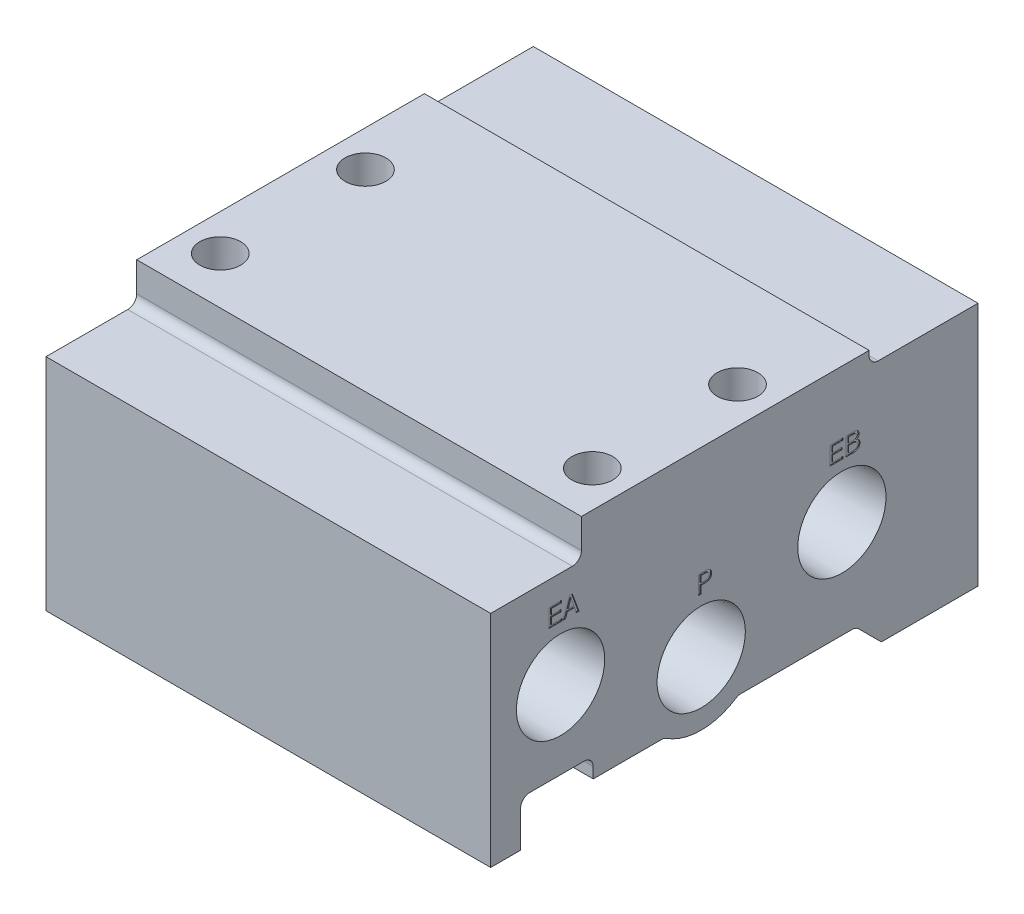
SolidWorks part; units mm, degrees
material "6061-T6 (SS)"
ref_plane "Front" through (0, 0, 0) normal (0, 0, 1) x (1, 0, 0)
ref_plane "Top" through (0, 0, 0) normal (0, 1, 0) x (1, 0, 0)
ref_plane "Right" through (0, 0, 0) normal (1, 0, 0) x (0, 0, -1)
sketch "Alum Ext Sketch" plane through (0, 0, 0) normal (1, 0, 0) x (0, 0, -1)
  line L1 (-26.85, 0) -> (26.85, 0)
  line L2 (-26.85, 0) -> (-26.85, -28.5)
  line L4 (26.85, 0) -> (26.85, -28.5)
  line L7 (0, 5.7104) -> (0, -31.2342) construction
  line L8 (-26.85, -28.5) -> (26.85, -28.5)
  dimension "Depth" = 53.7
  dimension "Height" = 28.5
extrude "Alum Ext" add sketch "Alum Ext Sketch" against normal up to surface (49 mm away)
sketch "Bottom_Profile 20 Sketch" [suppressed] plane through (0, 0, 0) normal (1, 0, 0) x (0, 0, -1)
  line L0 (-1, 0) -> (-1, -38.4475) construction
  line L1 (-21.54, -20) -> (-21.54, -13.45)
  line L2 (-24.5, -20) -> (24.5, -20) construction
  line L3 (-21.54, -13.45) -> (-21.1875, -13.45)
  line L4 (-13.8125, -13.45) -> (-4.6875, -13.45)
  line L5 (11.8125, -13.45) -> (2.6875, -13.45)
  line L6 (21.54, -13.45) -> (19.1875, -13.45)
  line L7 (21.54, -20) -> (21.54, -13.45)
  line L8 (24.5, -20) -> (24.5, 0) construction
  line L9 (-24.5, 0) -> (-24.5, -20) construction
  line L10 (24.5, 0) -> (-24.5, 0) construction
  line L11 (21.54, -16.725) -> (24.5, -16.725) construction
  line L12 (-21.54, -16.725) -> (-24.5, -16.725) construction
  line L13 (-24.5, -20) -> (-24.5, 0) construction
  line L14 (-21.54, -20) -> (21.54, -20)
  line L15 (-10.2716, -5) -> (-8.2284, -5)
  line L17 (-10.9481, -11.65) -> (-7.5519, -11.65)
  line L18 (-1, 9.9528) -> (-1, -11.3216) construction
  line L19 (8.9481, -11.65) -> (5.5519, -11.65)
  line L20 (8.2716, -5) -> (6.2284, -5)
  line L21 (24.5, 0) -> (-24.5, 0) construction
  arc A0 (-21.1875, -13.45) -> (-13.8125, -13.45) centre (-17.5, -7.5) ccw
  arc A1 (-4.6875, -13.45) -> (2.6875, -13.45) centre (-1, -7.5) ccw
  arc A2 (19.1875, -13.45) -> (11.8125, -13.45) centre (15.5, -7.5) cw
  arc A3 (-10.7535, -5.6333) -> (-11.3849, -10.9067) centre (-17.5, -7.5) cw
  arc A4 (-10.7535, -5.6333) -> (-10.2716, -5) centre (-10.2716, -5.5) cw
  arc A5 (-10.9481, -11.65) -> (-11.3849, -10.9067) centre (-10.9481, -11.15) cw
  arc A6 (-7.5519, -11.65) -> (-7.1151, -10.9067) centre (-7.5519, -11.15) ccw
  arc A7 (-7.7465, -5.6333) -> (-8.2284, -5) centre (-8.2284, -5.5) ccw
  arc A8 (-7.7465, -5.6333) -> (-7.1151, -10.9067) centre (-1, -7.5) ccw
  arc A9 (5.7465, -5.6333) -> (5.1151, -10.9067) centre (-1, -7.5) cw
  arc A10 (5.7465, -5.6333) -> (6.2284, -5) centre (6.2284, -5.5) cw
  arc A11 (5.5519, -11.65) -> (5.1151, -10.9067) centre (5.5519, -11.15) cw
  arc A12 (8.9481, -11.65) -> (9.3849, -10.9067) centre (8.9481, -11.15) ccw
  arc A13 (8.7535, -5.6333) -> (8.2716, -5) centre (8.2716, -5.5) ccw
  arc A14 (8.7535, -5.6333) -> (9.3849, -10.9067) centre (15.5, -7.5) ccw
  dimension "D1" = 23.5
  dimension "Wall_Radius" = 7
  dimension "D2" = 0.5
  dimension "D4" = 5
  dimension "D3" = 1.8
  dimension "Thickness" = 2.96
  dimension "Port_Loc_Z" = 16.5
  dimension "Port_Loc_Y" = 12.5
  dimension "Body_Thickness" = 13.45
extrude "Bottom_Profile 20" [suppressed] cut sketch "Bottom_Profile 20 Sketch" against normal through all
fillet "Ext_Fillets" [suppressed] radius 0.25
sketch "MGT_Holes Sketch" plane through (0, 0, 0) normal (0, 1, 0) x (1, 0, 0)
  line L1 (-24.5, 26.85) -> (-24.5, -50.1534) construction
  line L2 (-49, 26.85) -> (0, 26.85) construction
  line L3 (0, 0) -> (0, 12.4211) construction
  line L4 (-49, -26.85) -> (0, -26.85) construction
  line L6 (-49, -26.85) -> (-49, 26.85) construction
  circle A0 centre (-45, 4.35) radius 2.25
  circle A1 centre (-45, -11.65) radius 2.25
  circle A4 centre (-4, 4.35) radius 2.25
  circle A5 centre (-4, -11.65) radius 2.25
  dimension "Dia" = 4.5
  dimension "Loc_X" = 4
  dimension "Loc_Z" = 15.2
  dimension "C_2_C" = 16
extrude "MGT_Holes" cut sketch "MGT_Holes Sketch" against normal through all
sketch "Top_Profile_41 Sketch" plane through (0, 0, 0) normal (1, 0, 0) x (0, 0, -1)
  line L0 (-26.85, -4.25) -> (-16.85, -4.25)
  line L1 (-16.85, -4.25) -> (-16.85, 0)
  line L2 (26.85, 0) -> (-26.85, 0) construction
  line L3 (14.85, 0) -> (14.85, -1.5)
  line L4 (14.85, -1.5) -> (26.85, -1.5)
  line L5 (26.85, -28.5) -> (26.85, 0) construction
  line L6 (-26.85, -28.5) -> (26.85, -28.5) construction
  line L7 (-26.85, 0) -> (-26.85, -28.5) construction
  line L8 (26.85, -1.5) -> (26.85, 0)
  line L9 (-26.85, 0) -> (-26.85, -4.25)
  line L10 (26.85, 0) -> (14.85, 0)
  line L11 (-16.85, 0) -> (-26.85, 0)
  dimension "Back" = 12
  dimension "Back Height" = 27
  dimension "Front" = 10
  dimension "Front_Height" = 24.25
extrude "Top_Profile_41" cut sketch "Top_Profile_41 Sketch" against normal through all
sketch "Bottom_Profile_41 Sketch" plane through (0, 0, 0) normal (1, 0, 0) x (0, 0, -1)
  line L0 (16.2, -28.5) -> (13.4, -25.7)
  line L1 (-26.85, -28.5) -> (26.85, -28.5) construction
  line L2 (13.4, -25.7) -> (0.4132, -25.7)
  line L3 (-15.55, -25.7) -> (-15.55, -23.5)
  line L4 (-15.55, -23.5) -> (-23.55, -23.5)
  line L5 (-23.55, -23.5) -> (-23.55, -28.5)
  line L6 (26.85, -28.5) -> (-26.85, -28.5) construction
  line L7 (26.85, -28.5) -> (26.85, -1.5) construction
  line L8 (-26.85, -4.25) -> (-26.85, -28.5) construction
  line L9 (-26.85, -28.5) -> (-26.85, -4.25) construction
  line L10 (-7.7132, -25.7) -> (-15.55, -25.7)
  line L11 (-23.55, -28.5) -> (16.2, -28.5)
  arc A0 (-7.7132, -25.7) -> (0.4132, -25.7) centre (-3.65, -20) ccw
  dimension "D1" = 8.5
  dimension "D2" = 23.2
  dimension "Radius" = 7
  dimension "Back_Width" = 13.45
  dimension "Back_Depth" = 2.8
  dimension "Front_Width" = 3.3
  dimension "Front_Depth" = 5
  dimension "Groove" = 8
  dimension "Angle" = 45
extrude "Bottom_Profile_41" cut sketch "Bottom_Profile_41 Sketch" against normal through all
fillet "Rounds_41" radius 1 7 edges at (-24.5, -4.25, 16.85) (-24.5, -1.5, -14.85) (-24.5, -25.7, -0.4132) (-24.5, -23.5, 23.55) (-24.5, -23.5, 15.55) (-24.5, -25.7, 7.7132) (-24.5, -25.7, -13.4)
sketch "Profile_42 Sketch" [suppressed] plane through (0, 0, 0) normal (1, 0, 0) x (0, 0, -1)
  line L0 (-13.9, -32) -> (-12.9, -31)
  line L1 (-27.85, -32) -> (27.85, -32) construction
  line L2 (-12.9, -31) -> (12.9, -31)
  line L3 (12.9, -31) -> (13.9, -32)
  line L4 (13.9, -32) -> (-13.9, -32)
  line L5 (0, 0) -> (0, -41.5568) construction
  dimension "Width" = 25.8
  dimension "Angle" = 90
  dimension "Depth" = 1
extrude "Profile_42" [suppressed] cut sketch "Profile_42 Sketch" against normal through all
fillet "Fillets_42" [suppressed] radius 0.5
sketch "20 Port Designations Sketch" [suppressed] plane through (2.9671, 0, 3.015) normal (0, 1, 0) x (0, 0, 1)
  line L0 (21.485, -51.4671) -> (-27.515, -51.4671) construction
  line L2 (-27.515, -51.4671) -> (-27.515, -2.9671) construction
  line L3 (21.485, -51.4671) -> (21.485, -2.9671) construction
  text T0 "EA"
  text T1 "P" font "Swis721 BT" height 3.5
  text T2 "EB" font "Swis721 BT" height 3.5
  dimension "D1" = 3
  dimension "D2" = 4
  dimension "D3" = 23
  dimension "D4" = 11
extrude "20 Port Designations" [suppressed] cut sketch "20 Port Designations Sketch" against normal blind 0.1
sketch "20 Port Designations2 Sketch" [suppressed] plane through (-31.3648, 0, 0.1552) normal (0, 1, 0) x (0, 0, -1)
  line L0 (24.6552, -31.3648) -> (-24.3448, -31.3648) construction
  line L1 (24.6552, 17.1352) -> (24.6552, -31.3648) construction
  line L2 (-24.3448, 17.1352) -> (-24.3448, -31.3648) construction
  text T0 "EB"
  text T1 "P"
  text T2 "EA"
  dimension "D1" = 3
  dimension "D2" = 26.5
  dimension "D3" = 4
  dimension "D4" = 11
extrude "20 Port Designations2" [suppressed] cut sketch "20 Port Designations2 Sketch" against normal blind 0.1
hole_wizard "Ports" positions "Ports Loc Sketch" profile "Ports Profile Sketch" size "1/8" standard "ISO"
sketch "Ports Loc Sketch" plane through (0, 0, 0) normal (1, 0, 0) x (0, 0, -1)
  line L1 (-3.65, -20) -> (-3.65, -0.9405) construction
  line L5 (-26.85, -28.5) -> (-23.55, -28.5) construction
  line L7 (-26.85, -4.25) -> (-26.85, -28.5) construction
  point P0 (-3.65, -20)
  point P1 (11.85, -14.9)
  point P3 (-19.15, -14.9)
  dimension "Loc_Z" = 23.2
  dimension "C_2_C-Z" = 15.5
  dimension "C_2_C-Y" = 8.5
  dimension "Loc_Y" = 13.6
sketch "Ports Profile Sketch" plane through (0, -20, 3.65) normal (0, 1, 0) x (0, 0, -1)
  line L0 (0, 0) -> (0, 22.45)
  line L1 (3.95, 18.5) -> (0, 22.45)
  line L2 (-3.95, 18.5) -> (0, 22.45) construction
  line L3 (3.95, 18.5) -> (3.95, 7.4)
  line L4 (3.95, 7.4) -> (4.633, 7.4)
  line L5 (4.633, 7.4) -> (4.864, 0)
  line L6 (-4.633, 7.4) -> (-4.864, 0) construction
  line L7 (4.864, 0) -> (0, 0)
  line L8 (0, -6.35) -> (0, 107.95) construction
  line L11 (-3.95, 7.4) -> (-4.633, 7.4) construction
  dimension "Tap Drill Dia." = 7.9
  dimension "Tap Drill Depth" = 18.5
  dimension "Thread Dia." = 9.728
  dimension "Thread Angle" = 3.576
  dimension "Thread Depth" = 7.4
  dimension "Drill Angle" = 90
hole_wizard "Ports Mirror" positions "Ports Mirror Loc Sketch" profile "Ports Mirror Profile Sketch" size "1/8" standard "ISO"
sketch "Ports Mirror Loc Sketch" plane through (-49, 0, 0) normal (-1, 0, 0) x (0, 0, 1)
  point P0 (-11.85, -14.9)
  point P1 (3.65, -20)
  point P4 (19.15, -14.9)
sketch "Ports Mirror Profile Sketch" plane through (-49, -14.9, -11.85) normal (0, 1, 0) x (0, 0, 1)
  line L0 (0, 0) -> (0, 15.885)
  line L1 (3.95, 11.935) -> (0, 15.885)
  line L2 (-3.95, 11.935) -> (0, 15.885) construction
  line L3 (3.95, 11.935) -> (3.95, 7.4)
  line L4 (3.95, 7.4) -> (4.633, 7.4)
  line L5 (4.633, 7.4) -> (4.864, 0)
  line L6 (-4.633, 7.4) -> (-4.864, 0) construction
  line L7 (4.864, 0) -> (0, 0)
  line L8 (0, -6.35) -> (0, 107.95) construction
  line L11 (-3.95, 7.4) -> (-4.633, 7.4) construction
  dimension "Tap Drill Dia." = 7.9
  dimension "Tap Drill Depth" = 11.935
  dimension "Thread Dia." = 9.728
  dimension "Thread Angle" = 3.576
  dimension "Thread Depth" = 7.4
  dimension "Drill Angle" = 90
hole_wizard "Pilot Ports" [suppressed] positions "Pilot Ports Loc Sketch" profile "Pilot Ports Profile Sketch" tap size "M5x0.8" standard "JIS"
sketch "Pilot Ports Loc Sketch" [suppressed] plane through (0, 0, 0) normal (1, 0, 0) x (0, 0, -1)
  line L1 (14.1071, -32) -> (27.85, -32) construction
  circle A0 centre (-4.65, -24) radius 4.864 construction
  point P0 (14.75, -4)
  point P1 (-19.35, -4)
  dimension "D2" = 19.4
  dimension "D3" = 14.7
  dimension "D1" = 28
sketch "Pilot Ports Profile Sketch" [suppressed] plane through (0, -4, -14.75) normal (0, 1, 0) x (0, 0, -1)
  line L0 (0, 0) -> (0, 13.6618)
  line L1 (0, 13.6618) -> (2.1, 12.4)
  line L2 (2.1, 12.4) -> (2.1, 10)
  line L3 (2.1, 10) -> (2.5, 10)
  line L4 (2.5, 10) -> (2.5, 0)
  line L5 (2.5, 0) -> (0, 0)
  line L10 (0, 13.6618) -> (-2.1, 12.4) construction
  line L11 (0, -6.35) -> (0, 107.95) construction
  dimension "Tap Drill Dia." = 4.2
  dimension "Tap Drill Depth" = 12.4
  dimension "Thread Major Dia." = 5
  dimension "Thread Depth" = 10
  dimension "Drill Angle" = 118
hole_wizard "Pilot Ports Mirror" [suppressed] positions "Pilot Ports Mirror Loc Sketch" profile "Pilot Ports Mirror Profile Sketch" tap size "M5" standard "ISO"
sketch "Pilot Ports Mirror Loc Sketch" [suppressed] plane through (-101.5, 0, 0) normal (-1, 0, 0) x (0, 0, 1)
  point P0 (19.35, -4)
  point P1 (-14.75, -4)
sketch "Pilot Ports Mirror Profile Sketch" [suppressed] plane through (-101.5, -4, 19.35) normal (0, 1, 0) x (0, 0, 1)
  line L0 (0, 0) -> (0, 13.6618)
  line L1 (0, 13.6618) -> (2.1, 12.4)
  line L2 (2.1, 12.4) -> (2.1, 10)
  line L3 (2.1, 10) -> (2.5, 10)
  line L4 (2.5, 10) -> (2.5, 0)
  line L5 (2.5, 0) -> (0, 0)
  line L10 (0, 13.6618) -> (-2.1, 12.4) construction
  line L11 (0, -6.35) -> (0, 107.95) construction
  dimension "Tap Drill Dia." = 4.2
  dimension "Tap Drill Depth" = 12.4
  dimension "Thread Major Dia." = 5
  dimension "Thread Depth" = 10
  dimension "Drill Angle" = 118
sketch "41,42 Port Labels1 Sketch" plane through (-49, 0, 0) normal (-1, 0, 0) x (0, 0, 1)
  text T0 "EB" font "Swis721 BT" height 2
  text T1 "P" font "Swis721 BT" height 2
  text T2 "EA" font "Swis721 BT" height 2
  dimension "D1" = 1.5
  dimension "D2" = 1.5
  dimension "D3" = 6
  dimension "D4" = 6
  dimension "D5" = 6
  dimension "D6" = 0.5
extrude "41,42 Port Labels1" cut sketch "41,42 Port Labels1 Sketch" against normal blind 0.1
sketch "41,42 Port Labels2 Sketch" plane through (0, 0, 0) normal (1, 0, 0) x (0, 0, -1)
  text T0 "EA" font "Swis721 BT" height 2
  text T1 "P" font "Swis721 BT" height 2
  text T2 "EB" font "Swis721 BT" height 2
  dimension "D1" = 6
  dimension "D2" = 6
  dimension "D3" = 0.5
  dimension "D4" = 6
  dimension "D5" = 1.5
  dimension "D6" = 1.5
extrude "41,42 Port Labels2" cut sketch "41,42 Port Labels2 Sketch" against normal blind 0.1
sketch "42 Pilot Labels1 Sketch" [suppressed] plane through (-101.5, 0, 0) normal (-1, 0, 0) x (0, 0, 1)
  text T0 "PE" font "Swis721 BT" height 2
  text T1 "X" font "Swis721 BT" height 2
extrude "42 Pilot Labels1" [suppressed] cut sketch "42 Pilot Labels1 Sketch" against normal blind 0.1
sketch "42 Pilot Labels2 Sketch" [suppressed] plane through (0, 0, 0) normal (1, 0, 0) x (0, 0, -1)
  text T0 "X" font "Swis721 BT" height 2
  text T1 "PE" font "Swis721 BT" height 2
extrude "42 Pilot Labels2" [suppressed] cut sketch "42 Pilot Labels2 Sketch" against normal blind 0.1
sketch "41,42 A,B Labels Sketch" plane through (0, 0, -26.85) normal (0, 0, 1) x (1, 0, 0)
  line L0 (-49, -28.5) -> (0, -28.5) construction
  line L1 (-49, -1.5) -> (-49, -28.5) construction
  line L2 (0, -28.5) -> (0, -1.5) construction
  line L3 (-49, -28.5) -> (0, -28.5) construction
  text T0 "A"
  text T1 "B"
  text T2 "A"
  text T3 "B"
  point P12 (-49, -15)
  dimension "D1" = 5
  dimension "D2" = 11
  dimension "D3" = 1
  dimension "D4" = 18.5
  dimension "D5" = 8
  dimension "D6" = 4.5
extrude "41,42 A,B Labels" cut sketch "41,42 A,B Labels Sketch" along normal blind 0.1
